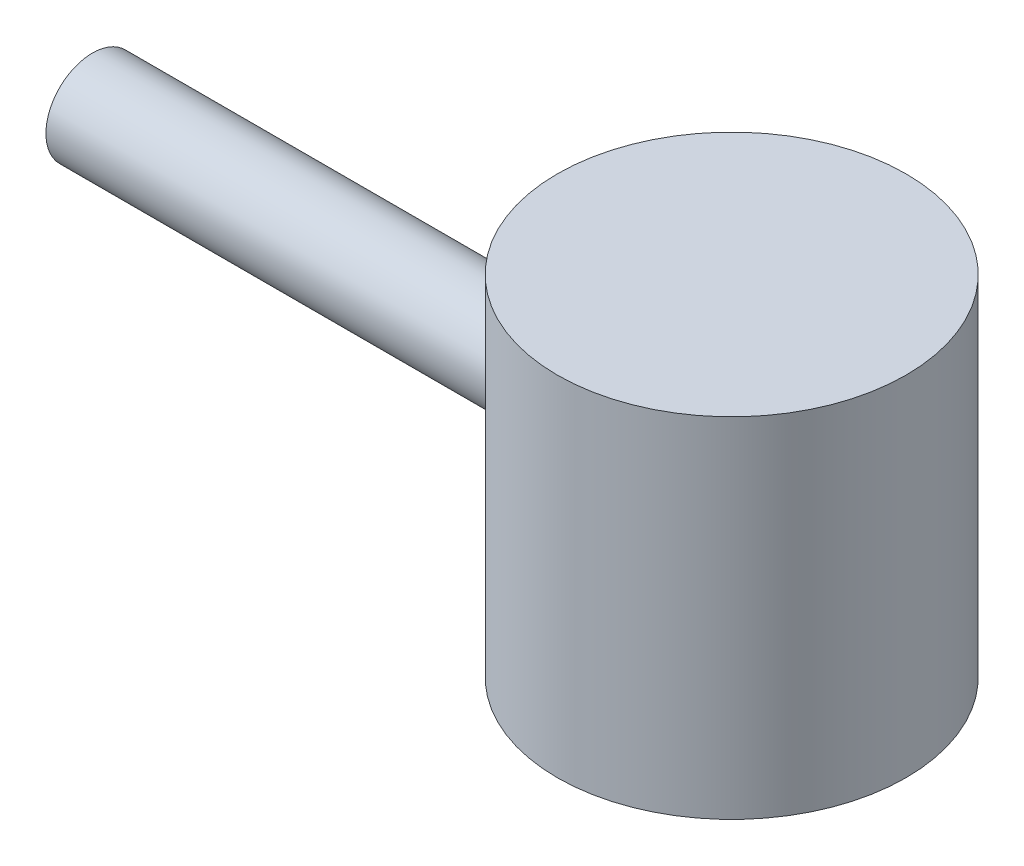
SolidWorks part; units mm, degrees
ref_plane "Front Plane" through (0, 0, 0) normal (0, 0, 1) x (1, 0, 0)
ref_plane "Top Plane" through (0, 0, 0) normal (0, 1, 0) x (1, 0, 0)
ref_plane "Right Plane" through (0, 0, 0) normal (1, 0, 0) x (0, 0, -1)
sketch "Sketch1" plane through (0, 0, 0) normal (0, 1, 0) x (1, 0, 0)
  circle A0 centre (0, 0) radius 7.5
  dimension "D1" = 15
extrude "Boss-Extrude1" add sketch "Sketch1" along normal mid plane 15 contours A0
sketch "Sketch2" plane through (0, 0, 0) normal (1, 0, 0) x (0, 0, -1)
  circle A0 centre (0, 0) radius 2
  dimension "D1" = 4
extrude "Boss-Extrude2" add sketch "Sketch2" against normal blind 27.5
